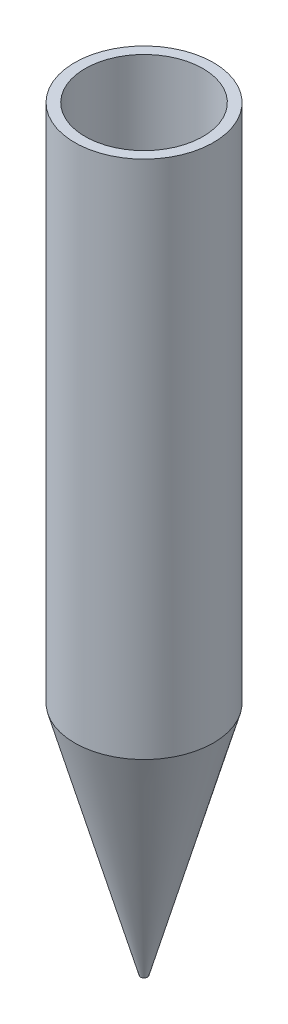
SolidWorks part; units mm, degrees
ref_plane "Front Plane" through (0, 0, 0) normal (0, 0, 1) x (1, 0, 0)
ref_plane "Top Plane" through (0, 0, 0) normal (0, 1, 0) x (1, 0, 0)
ref_plane "Right Plane" through (0, 0, 0) normal (1, 0, 0) x (0, 0, -1)
sketch "Sketch3" plane through (0, 0, 0) normal (0, 0, 1) x (1, 0, 0)
  line L0 (0, 0) -> (0, 68) construction
  line L1 (0, 0) -> (1, 0)
  line L2 (1, 0) -> (20, 68)
  line L3 (20, 68) -> (20, 218)
  line L4 (17, 218) -> (17, 68)
  line L5 (17, 68) -> (0, 68)
  line L6 (17, 218) -> (20, 218)
  line L7 (0, 0) -> (0, 68)
  dimension "D2" = 1
  dimension "D3" = 68
  dimension "D4" = 20
  dimension "D5" = 15.611
  dimension "D6" = 150
  dimension "D7" = 3
  dimension "D8" = 68
revolve "Revolve1" add sketch "Sketch3" angle 360 about L0
